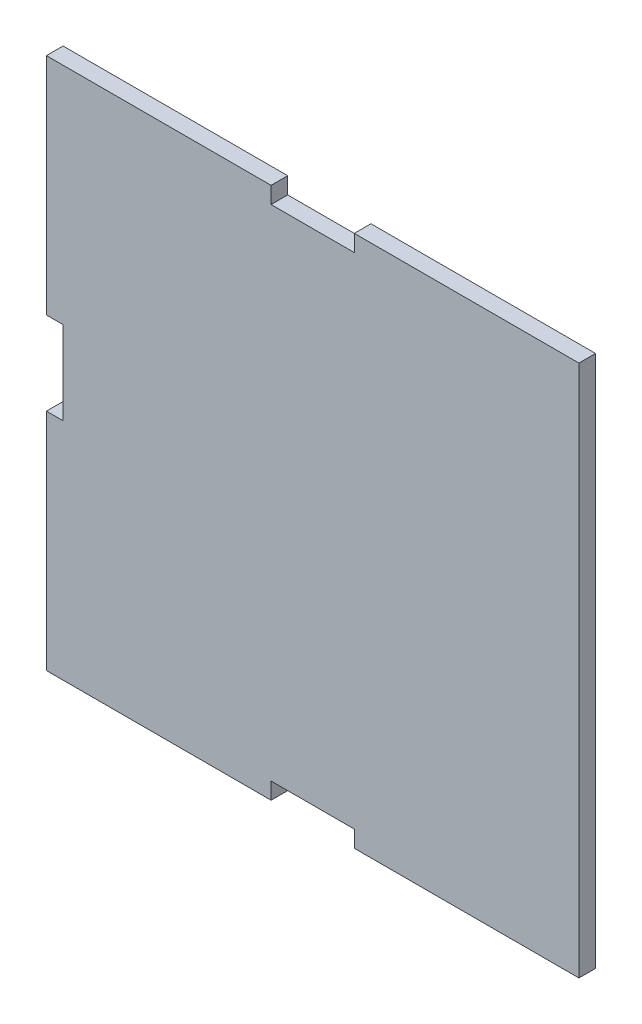
SolidWorks part; units mm, degrees
ref_plane "前视基准面" through (0, 0, 0) normal (0, 0, 1) x (1, 0, 0)
ref_plane "上视基准面" through (0, 0, 0) normal (0, 1, 0) x (1, 0, 0)
ref_plane "右视基准面" through (0, 0, 0) normal (1, 0, 0) x (0, 0, -1)
sketch "草图1" plane through (0, 0, 0) normal (0, 0, 1) x (1, 0, 0)
  line L0 (16.9744, 42.2051) -> (2.9744, 42.2051)
  line L1 (16.9744, 42.2051) -> (-10.0256, 42.2051)
  line L2 (16.9744, 42.2051) -> (16.9744, 15.2051)
  line L3 (16.9744, -21.7949) -> (-10.0256, -21.7949)
  line L4 (-47.0256, 42.2051) -> (-47.0256, 15.2051)
  line L5 (2.9744, 42.2051) -> (-5.2982, 42.2051)
  line L7 (-10.0256, 42.2051) -> (-10.0256, 40.2051)
  line L8 (-10.0256, 40.2051) -> (-20.0256, 40.2051)
  line L9 (-20.0256, 40.2051) -> (-20.0256, 42.2051)
  line L10 (-10.0256, -21.7949) -> (-10.0256, -19.7949)
  line L11 (-10.0256, -19.7949) -> (-20.0256, -19.7949)
  line L12 (-20.0256, -19.7949) -> (-20.0256, -21.7949)
  line L13 (-20.0256, -21.7949) -> (-47.0256, -21.7949)
  line L14 (-47.0256, 15.2051) -> (-45.0256, 15.2051)
  line L15 (-45.0256, 15.2051) -> (-45.0256, 5.2051)
  line L16 (-45.0256, 5.2051) -> (-47.0256, 5.2051)
  line L20 (-20.0256, 42.2051) -> (-47.0256, 42.2051)
  line L21 (-47.0256, 5.2051) -> (-47.0256, -21.7949)
  line L22 (16.9744, 5.2051) -> (16.9744, -21.7949)
  line L23 (16.9744, 5.2051) -> (16.9744, 15.2051)
  point P9 (-15.0256, 42.2051)
  dimension "D1" = 64
  dimension "D2" = 64
  dimension "D3" = 14
  dimension "D4" = 64
extrude "凸台-拉伸1" add sketch "草图1" along normal blind 2
